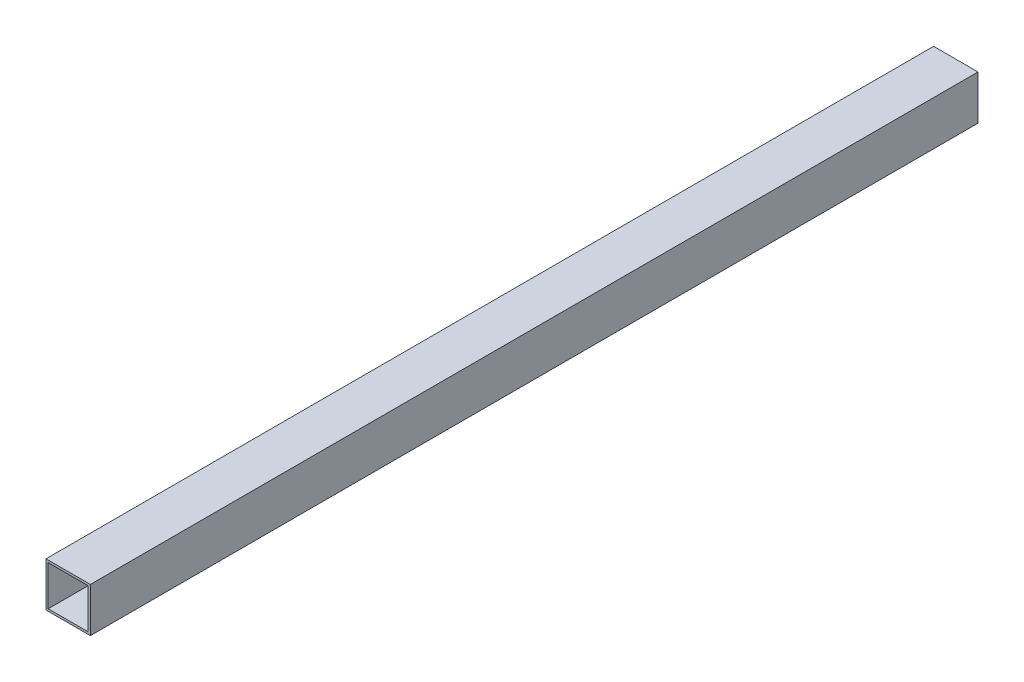
SolidWorks part; units mm, degrees
material "6061 Alloy"
ref_plane "Front Plane" through (0, 0, 0) normal (0, 0, 1) x (1, 0, 0)
ref_plane "Top Plane" through (0, 0, 0) normal (0, 1, 0) x (1, 0, 0)
ref_plane "Right Plane" through (0, 0, 0) normal (1, 0, 0) x (0, 0, -1)
sketch "Sketch3" plane through (0, 0, 0) normal (0, 0, 1) x (1, 0, 0)
  line L0 (-9, 9) -> (9, 9)
  line L1 (-10, -10) -> (10, -10)
  line L2 (-10, -10) -> (-10, 10)
  line L3 (-10, 10) -> (10, 10)
  line L4 (10, -10) -> (10, 10)
  line L5 (-10, -10) -> (10, 10) construction
  line L6 (-10, 10) -> (10, -10) construction
  line L7 (9, -9) -> (9, 9)
  line L8 (-9, -9) -> (9, -9)
  line L9 (-9, -9) -> (-9, 9)
  point P0 (0, 0)
  dimension "D1" = 20
  dimension "D2" = 20
  dimension "D3" = 1
extrude "Boss-Extrude1" add sketch "Sketch3" along normal blind 400
